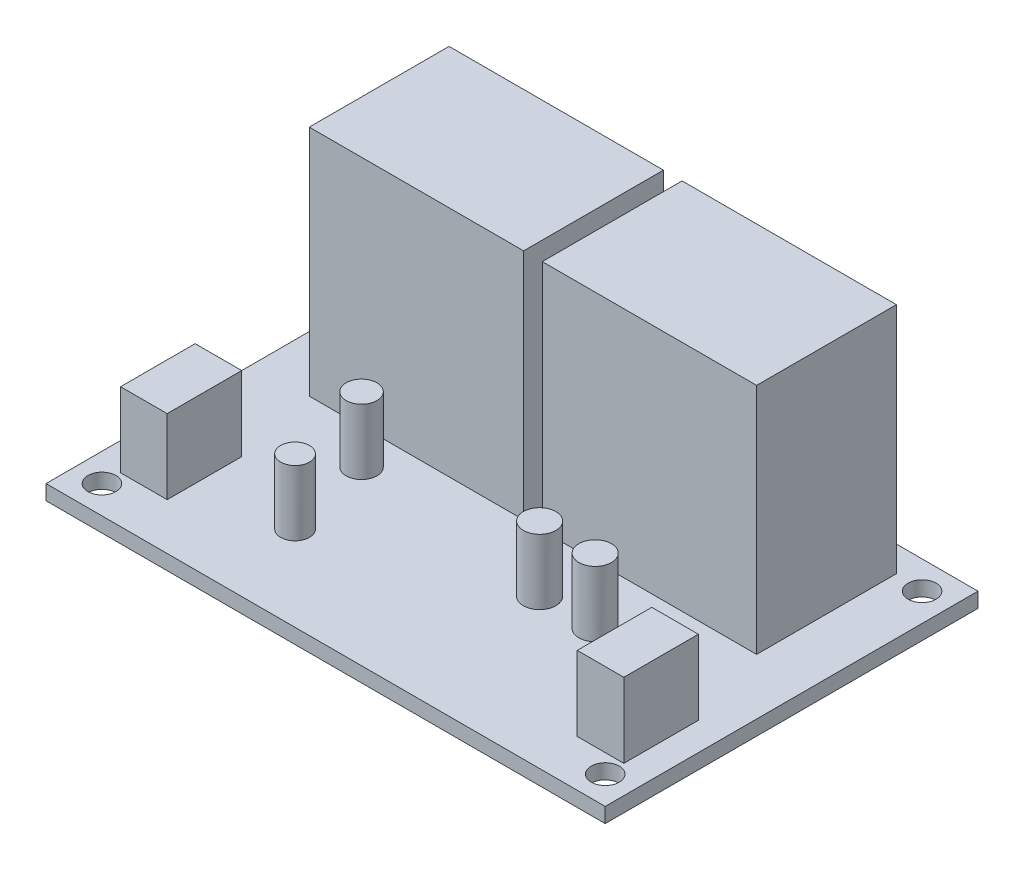
SolidWorks part; units mm, degrees
ref_plane "Front Plane" through (0, 0, 0) normal (0, 0, 1) x (1, 0, 0)
ref_plane "Top Plane" through (0, 0, 0) normal (0, 1, 0) x (1, 0, 0)
ref_plane "Right Plane" through (0, 0, 0) normal (1, 0, 0) x (0, 0, -1)
sketch "Sketch1" plane through (0, 0, 0) normal (0, 1, 0) x (1, 0, 0)
  line L1 (-30, -20) -> (30, -20)
  line L2 (-30, -20) -> (-30, 20)
  line L3 (-30, 20) -> (30, 20)
  line L4 (30, -20) -> (30, 20)
  line L5 (-30, -20) -> (30, 20) construction
  line L6 (-30, 20) -> (30, -20) construction
  point P0 (0, 0)
  dimension "D1" = 60
  dimension "D2" = 40
extrude "Boss-Extrude1" add sketch "Sketch1" along normal blind 1.6
sketch "Sketch2" plane through (0, 1.6, 0) normal (0, 1, 0) x (1, 0, 0)
  line L1 (-24, 17.2469) -> (-1, 17.2469)
  line L2 (-24, 17.2469) -> (-24, 2.2469)
  line L3 (-24, 2.2469) -> (-1, 2.2469)
  line L4 (-1, 17.2469) -> (-1, 2.2469)
  line L5 (-24, 17.2469) -> (-1, 2.2469) construction
  line L6 (-24, 2.2469) -> (-1, 17.2469) construction
  line L7 (1, 17.2469) -> (24, 17.2469)
  line L8 (1, 17.2469) -> (1, 2.2469)
  line L9 (1, 2.2469) -> (24, 2.2469)
  line L10 (24, 17.2469) -> (24, 2.2469)
  line L11 (1, 17.2469) -> (24, 2.2469) construction
  line L12 (1, 2.2469) -> (24, 17.2469) construction
  point P0 (-12.5, 9.7469)
  point P5 (12.5, 9.7469)
  dimension "D1" = 15
  dimension "D2" = 23
  dimension "D3" = 23
  dimension "D4" = 15
  dimension "D5" = 2
  dimension "D6" = 1
extrude "Boss-Extrude2" add sketch "Sketch2" along normal blind 25
sketch "Sketch3" plane through (0, 1.6, 0) normal (0, 1, 0) x (1, 0, 0)
  line L0 (-30, 20) -> (-30, -20) construction
  line L1 (-27, -7) -> (-22, -7)
  line L2 (-27, -7) -> (-27, -15)
  line L3 (-27, -15) -> (-22, -15)
  line L4 (-22, -7) -> (-22, -15)
  line L5 (-27, -7) -> (-22, -15) construction
  line L6 (-27, -15) -> (-22, -7) construction
  line L7 (22, -7) -> (27, -7)
  line L8 (22, -7) -> (22, -15)
  line L9 (22, -15) -> (27, -15)
  line L10 (27, -7) -> (27, -15)
  line L11 (22, -7) -> (27, -15) construction
  line L12 (22, -15) -> (27, -7) construction
  line L13 (30, -20) -> (30, 20) construction
  line L14 (-30, -20) -> (30, -20) construction
  point P0 (-24.5, -11)
  point P5 (24.5, -11)
  dimension "D1" = 8
  dimension "D2" = 5
  dimension "D3" = 8
  dimension "D4" = 5
  dimension "D5" = 3
  dimension "D6" = 3
  dimension "D7" = 5
extrude "Boss-Extrude3" add sketch "Sketch3" along normal blind 8
sketch "Sketch4" plane through (0, 1.6, 0) normal (0, 1, 0) x (1, 0, 0)
  circle A0 centre (-14.6096, -1.5344) radius 1.6516
  circle A1 centre (6.959, -3.9982) radius 1.75
  circle A2 centre (-12.4052, -10.8708) radius 1.5464
  circle A3 centre (12.9239, -3.9982) radius 1.75
  dimension "D1" = 3.5
  dimension "D2" = 3.5
extrude "Boss-Extrude4" add sketch "Sketch4" along normal blind 7
sketch "Sketch5" plane through (0, 1.6, 0) normal (0, 1, 0) x (1, 0, 0)
  line L0 (-30, 20) -> (-30, -20) construction
  line L1 (30, 20) -> (-30, 20) construction
  line L2 (30, -20) -> (30, 20) construction
  line L3 (-30, -20) -> (30, -20) construction
  circle A0 centre (-27, 17) radius 1.5
  circle A1 centre (-27, -17) radius 1.5
  circle A2 centre (27, -17) radius 1.5
  circle A3 centre (27, 17) radius 1.5
  dimension "D1" = 3
  dimension "D2" = 3
  dimension "D3" = 3
  dimension "D4" = 3
  dimension "D5" = 3
  dimension "D6" = 3
  dimension "D7" = 3
  dimension "D8" = 3
extrude "Cut-Extrude1" cut sketch "Sketch5" against normal up to next
